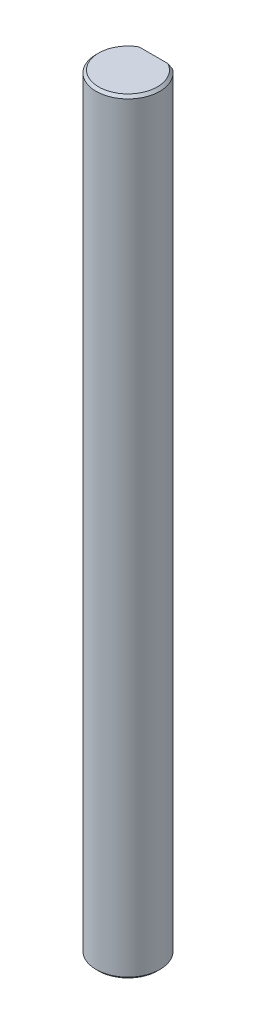
SolidWorks part; units mm, degrees
ref_plane "Alzado" through (0, 0, 0) normal (0, 0, 1) x (1, 0, 0)
ref_plane "Planta" through (0, 0, 0) normal (0, 1, 0) x (1, 0, 0)
ref_plane "Vista lateral" through (0, 0, 0) normal (1, 0, 0) x (0, 0, -1)
sketch "Croquis1" plane through (0, 0, 0) normal (0, 1, 0) x (1, 0, 0)
  circle A0 centre (0, 0) radius 2.5
  dimension "D1" = 5
extrude "Saliente-Extruir1" add sketch "Croquis1" along normal blind 60 contours A0
sketch "Croquis2" plane through (0, 60, 0) normal (0, 1, 0) x (1, 0, 0)
  line L0 (-1.5, 2) -> (1.5, 2)
  line L1 (0, -2.5) -> (0, 2) construction
  circle A0 centre (0, 0) radius 2.5 construction
  arc A1 (1.5, 2) -> (-1.5, 2) centre (0, 0) ccw
  dimension "D1" = 4.5
extrude "Cortar-Extruir1" cut sketch "Croquis2" against normal blind 10
chamfer "Chaflán1" distance 0.2 angle 45 2 edges at (0, 0, 2.5) (0, 60, 2.5)
